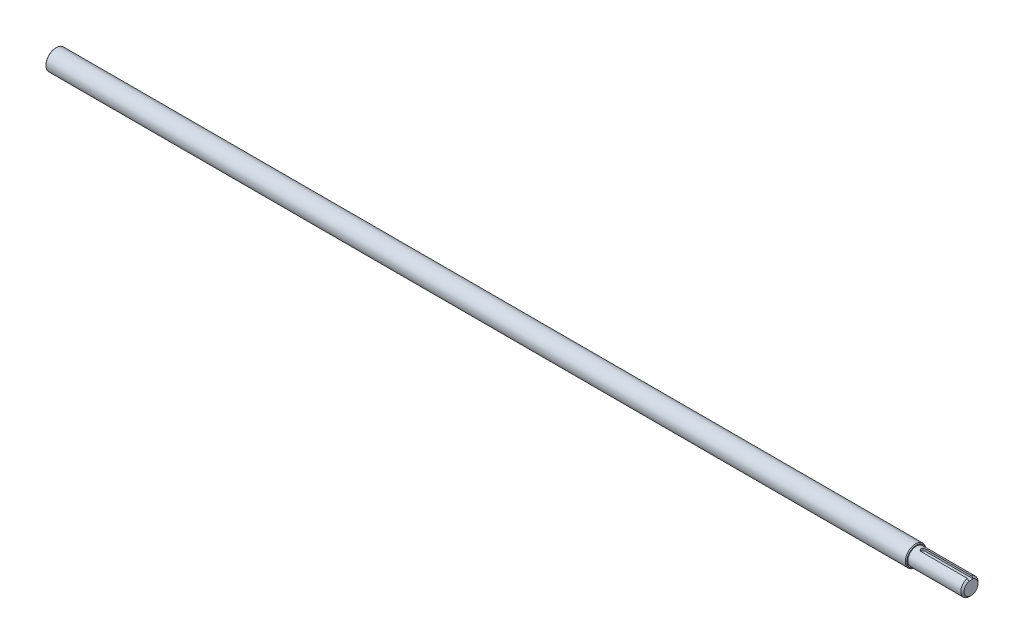
SolidWorks part; units mm, degrees
ref_plane "Front Plane" through (0, 0, 0) normal (0, 0, 1) x (1, 0, 0)
ref_plane "Top Plane" through (0, 0, 0) normal (0, 1, 0) x (1, 0, 0)
ref_plane "Right Plane" through (0, 0, 0) normal (1, 0, 0) x (0, 0, -1)
sketch "Sketch1" plane through (0, 0, 0) normal (1, 0, 0) x (0, 0, -1)
  circle A0 centre (0, 0) radius 4.7625 construction
  circle A2 centre (0, 0) radius 4.7879 construction
  dimension "Diameter" = 9.525
  dimension "Finish Thickness" = 0.0254
sketch "Sketch2" plane through (0, 0, 0) normal (0, 0, 1) x (1, 0, 0)
  line L0 (0, 0) -> (304.8, 0) construction
  line L1 (0, 0) -> (-304.8, 0) construction
  line L2 (304.8, 0) -> (304.8, 4.7625) construction
  line L3 (304.8, 0) -> (304.8, -4.7625) construction
  line L4 (304.8, 4.7625) -> (0, 4.7625) construction
  line L7 (0, 4.7625) -> (-304.8, 4.7625) construction
  line L8 (-304.8, 4.7625) -> (-304.8, 0) construction
  point P5 (-254, 0)
  point P8 (254, 0)
  dimension "Length" = 609.6
  dimension "D1" = 50.8
  dimension "D2" = 50.8
sketch "Sketch4" plane through (0, 0, 0) normal (1, 0, 0) x (0, 0, -1)
  circle A0 centre (0, 0) radius 4.7625 construction
  circle A1 centre (0, 0) radius 4.7625
extrude "Boss-Extrude1" add sketch "Sketch4" along normal up to vertex (304.8 mm away) and the other way up to vertex (304.8 mm away) up to point (304.8, 0, 0) other way up to point (-304.8, 0, 0)
chamfer "Chamfer1" distance 0.2476 angle 45 2 edges at (-304.8, 0, -4.7625) (304.8, 0, -4.7625)
sketch "Sketch5" plane through (0, 0, 0) normal (0, 0, 1) x (1, 0, 0)
  line L0 (304.8, 0) -> (120.65, 0)
  line L1 (304.8, -4.5149) -> (304.8, 4.5149) construction
  line L2 (120.65, 0) -> (120.65, 3.238)
  line L3 (120.65, 3.238) -> (119.888, 4)
  line L4 (119.888, 4) -> (95.25, 4)
  line L5 (95.25, 4) -> (95.25, 4.3815)
  line L6 (95.25, 4.3815) -> (94.869, 4.7625)
  line L7 (304.5524, 4.7625) -> (-304.5523, 4.7625) construction
  line L8 (94.869, 4.7625) -> (304.8, 4.7625)
  line L9 (304.8, 4.7625) -> (304.8, 0)
  line L10 (120.65, 0) -> (239.2618, 0) construction
  line L11 (-304.8, 4.5148) -> (-304.8, -4.5148) construction
  dimension "D1" = 8
  dimension "D2" = 425.45
  dimension "D3" = 45
  dimension "D4" = 0.762
  dimension "D5" = 0.381
  dimension "D6" = 45
  dimension "D7" = 25.4
revolve "Cut-Revolve1" cut sketch "Sketch5" angle 360 about L10
sketch "Sketch6" plane through (0, 0, 0) normal (0, 1, 0) x (1, 0, 0)
  line L0 (120.65, 0) -> (98.425, 0) construction
  line L1 (120.65, -3.238) -> (120.65, 3.238) construction
  line L2 (120.65, -1) -> (98.425, -1)
  line L3 (120.65, 1) -> (98.425, 1)
  arc A0 (120.65, -1) -> (120.65, 1) centre (120.65, 0) ccw
  arc A1 (98.425, 1) -> (98.425, -1) centre (98.425, 0) ccw
  point P5 (109.5375, 0)
  dimension "D1" = 2
  dimension "D2" = 22.225
extrude "Cut-Extrude1" cut sketch "Sketch6" against normal blind 1 from offset 4
equation "\"D1@Chamfer1\" = \"Diameter@Sketch1\" * .026"
equation "\"D2@Sketch2\" = \"D1@Sketch2\""
